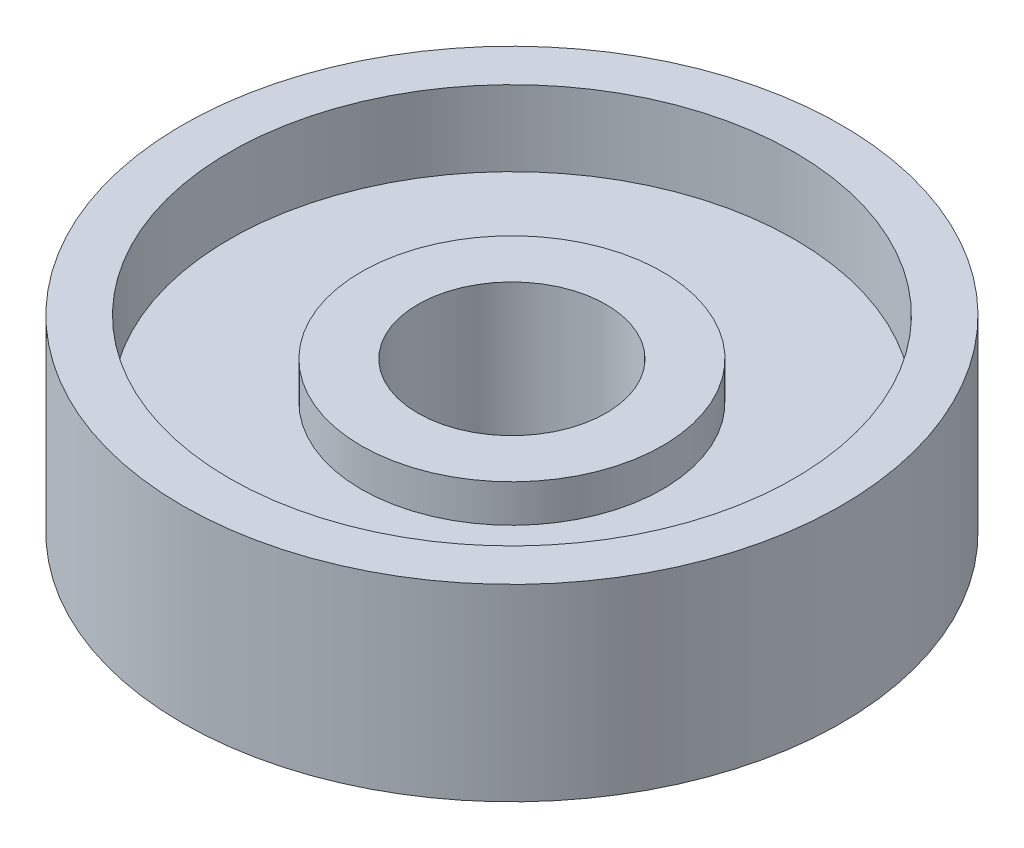
SolidWorks part; units mm, degrees
material "POM Acetal Copolymer"
ref_plane "Front Plane" through (0, 0, 0) normal (0, 0, 1) x (1, 0, 0)
ref_plane "Top Plane" through (0, 0, 0) normal (0, 1, 0) x (1, 0, 0)
ref_plane "Right Plane" through (0, 0, 0) normal (1, 0, 0) x (0, 0, -1)
sketch "Sketch3" plane through (0, 0, 0) normal (0, 1, 0) x (1, 0, 0)
  circle A0 centre (0, 0) radius 11.1125
  circle A1 centre (0, 0) radius 3.175
  dimension "D1" = 22.225
  dimension "D2" = 6.35
extrude "Boss-Extrude1" add sketch "Sketch3" along normal blind 6.35
sketch "Sketch4" plane through (0, 6.35, 0) normal (0, 1, 0) x (1, 0, 0)
  circle A0 centre (0, 0) radius 9.525
  dimension "D1" = 19.05
extrude "Cut-Extrude1" cut sketch "Sketch4" against normal blind 2.54
sketch "Sketch5" plane through (0, 3.81, 0) normal (0, 1, 0) x (1, 0, 0)
  circle A0 centre (0, 0) radius 5.08
  circle A1 centre (0, 0) radius 3.175
  dimension "D1" = 10.16
extrude "Boss-Extrude2" add sketch "Sketch5" along normal blind 1.27
